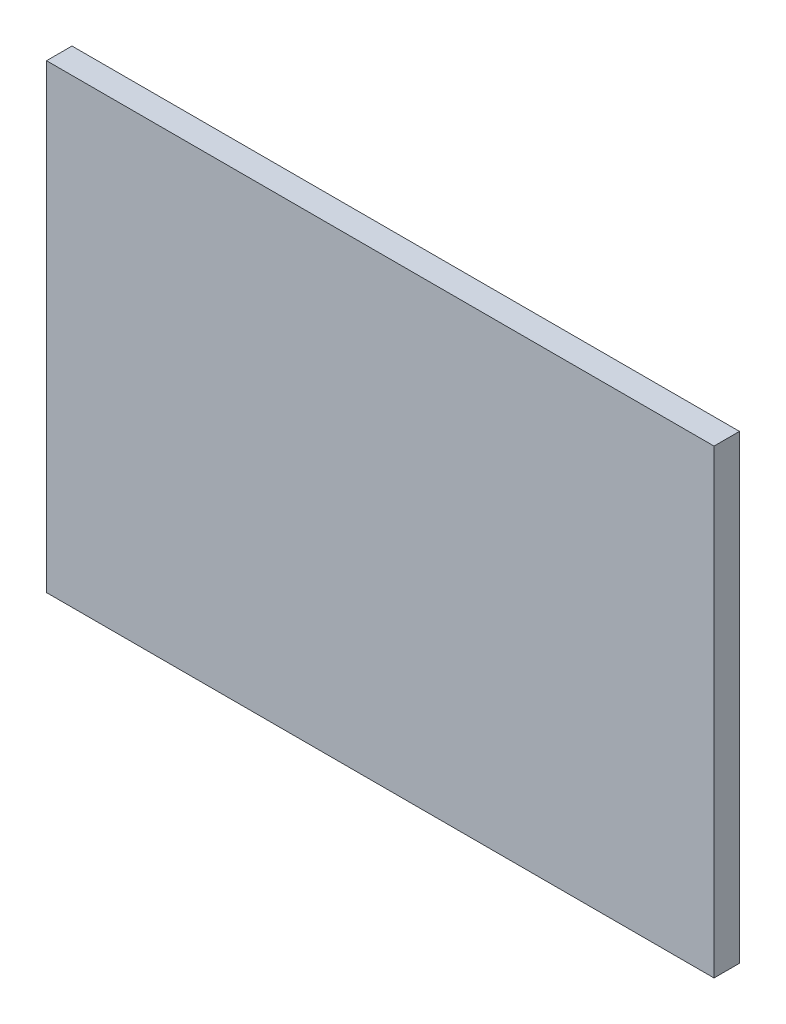
SolidWorks part; units mm, degrees
ref_plane "Ön Düzlem" through (0, 0, 0) normal (0, 0, 1) x (1, 0, 0)
ref_plane "Üst Düzlem" through (0, 0, 0) normal (0, 1, 0) x (1, 0, 0)
ref_plane "Sağ Düzlem" through (0, 0, 0) normal (1, 0, 0) x (0, 0, -1)
sketch "Çizim1" plane through (0, 0, 0) normal (0, 0, 1) x (1, 0, 0)
  line L1 (-74.3494, 45.9069) -> (32.2246, 45.9069)
  line L2 (-74.3494, 45.9069) -> (-74.3494, -27.6442)
  line L3 (-74.3494, -27.6442) -> (32.2246, -27.6442)
  line L4 (32.2246, 45.9069) -> (32.2246, -27.6442)
extrude "Yükseklik-Ekstrüzyon1" add sketch "Çizim1" along normal blind 4.064
